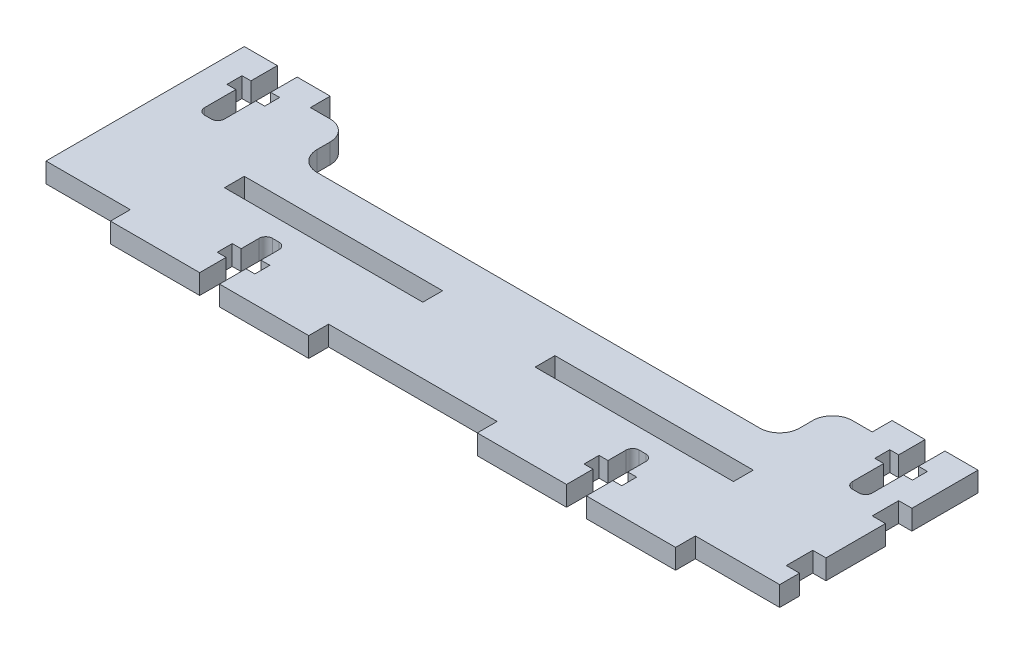
SolidWorks part; units mm, degrees
ref_plane "Plano frontal" through (0, 0, 0) normal (0, 0, 1) x (1, 0, 0)
ref_plane "Plano superior" through (0, 0, 0) normal (0, 1, 0) x (1, 0, 0)
ref_plane "Plano direito" through (0, 0, 0) normal (1, 0, 0) x (0, 0, -1)
sketch "Sketch1" plane through (0, 0, 0) normal (0, 1, 0) x (1, 0, 0)
  line L1 (-55.5, 15) -> (55.5, 15)
  line L2 (-55.5, 15) -> (-55.5, -15)
  line L3 (-55.5, -15) -> (55.5, -15)
  line L4 (55.5, 15) -> (55.5, -15)
  point P4 (0, 15)
  point P6 (-55.5, 0)
  dimension "D1" = 111
  dimension "D2" = 30
extrude "Boss-Extrude1" add sketch "Sketch1" along normal mid plane 3
sketch "Sketch2" plane through (0, 0, 0) normal (0, 1, 0) x (1, 0, 0)
  line L5 (-55.5, -15) -> (55.5, -15) construction
  line L6 (-42.75, -15) -> (-12.75, -15)
  line L7 (-42.75, -15) -> (-42.75, -18)
  line L8 (-42.75, -18) -> (-12.75, -18)
  line L9 (-12.75, -15) -> (-12.75, -18)
  line L10 (0, -1.65) -> (0, 1.65) construction
  line L11 (12.75, -15) -> (12.75, -18)
  line L12 (42.75, -18) -> (12.75, -18)
  line L13 (42.75, -15) -> (42.75, -18)
  line L14 (42.75, -15) -> (12.75, -15)
  line L15 (0, 15) -> (0, -15) construction
  line L16 (55.5, 15) -> (-55.5, 15) construction
  line L17 (-55.5, 15) -> (-55.5, -15) construction
  dimension "D1" = 3
  dimension "D2" = 30
  dimension "D3" = 12.75
  dimension "D4" = 12.75
extrude "Boss-Extrude2" add sketch "Sketch2" along normal mid plane 3
sketch "Sketch5" plane through (0, 0, 0) normal (0, 1, 0) x (1, 0, 0)
  line L0 (-42.75, -18) -> (-12.75, -18) construction
  line L1 (-29.25, -18) -> (-26.25, -18)
  line L2 (-29.25, -18) -> (-29.25, -14)
  line L3 (-28.25, -8) -> (-27.25, -8)
  line L4 (-26.25, -18) -> (-26.25, -14)
  line L6 (-29.25, -11.73) -> (-29.25, -9)
  line L7 (-30.5969, -11.73) -> (-29.25, -11.73)
  line L8 (-30.5969, -11.73) -> (-30.5969, -14)
  line L9 (-30.5969, -14) -> (-29.25, -14)
  line L10 (-24.9, -11.73) -> (-24.9, -14)
  line L11 (-26.25, -11.73) -> (-24.9, -11.73)
  line L12 (-26.25, -11.73) -> (-26.25, -9)
  line L13 (-26.25, -14) -> (-24.9, -14)
  line L14 (0, -1.65) -> (0, 1.65) construction
  line L15 (26.25, -14) -> (24.9, -14)
  line L16 (26.25, -11.73) -> (26.25, -9)
  line L17 (26.25, -11.73) -> (24.9, -11.73)
  line L18 (24.9, -11.73) -> (24.9, -14)
  line L19 (30.5969, -14) -> (29.25, -14)
  line L20 (30.5969, -11.73) -> (30.5969, -14)
  line L21 (30.5969, -11.73) -> (29.25, -11.73)
  line L22 (29.25, -11.73) -> (29.25, -9)
  line L23 (26.25, -18) -> (26.25, -14)
  line L24 (28.25, -8) -> (27.25, -8)
  line L25 (29.25, -18) -> (29.25, -14)
  line L26 (29.25, -18) -> (26.25, -18)
  arc A0 (-27.25, -8) -> (-26.25, -9) centre (-27.25, -9) cw
  arc A1 (-29.25, -9) -> (-28.25, -8) centre (-28.25, -9) cw
  arc A2 (29.25, -9) -> (28.25, -8) centre (28.25, -9) ccw
  arc A3 (27.25, -8) -> (26.25, -9) centre (27.25, -9) ccw
  point P8 (-27.75, -18)
  point P9 (-27.75, -18)
  point P22 (-29.25, -8)
  point P41 (29.25, -8)
  dimension "D8" = 1
  dimension "D2" = 10
  dimension "D3" = 3
  dimension "D4" = 2.27
  dimension "D5" = 1.3469
  dimension "D6" = 1.35
  dimension "D7" = 4
extrude "Cut-Extrude2" cut sketch "Sketch5" against normal through all both and the other way through all
sketch "Sketch6" plane through (0, 0, 0) normal (0, 1, 0) x (1, 0, 0)
  line L0 (55.5, -15) -> (55.5, 15) construction
  line L1 (55.5, -8) -> (53.5, -8)
  line L2 (55.5, -8) -> (55.5, -12)
  line L3 (55.5, -12) -> (53.5, -12)
  line L4 (53.5, -8) -> (53.5, -12)
  line L7 (42.75, -15) -> (55.5, -15) construction
  line L17 (53.5, 5) -> (55.5, 5)
  line L18 (53.5, 5) -> (53.5, 1)
  line L19 (53.5, 1) -> (55.5, 1)
  line L20 (55.5, 5) -> (55.5, 1)
  dimension "D1" = 4
  dimension "D2" = 2
  dimension "D3" = 3
  dimension "D4" = 9
extrude "Cut-Extrude3" cut sketch "Sketch6" against normal through all both and the other way through all
sketch "Sketch7" plane through (0, 1.5, 0) normal (0, 1, 0) x (1, 0, 0)
  line L9 (-38.5, -2) -> (-8.5, -2)
  line L10 (-38.5, -2) -> (-38.5, -5)
  line L11 (-38.5, -5) -> (-8.5, -5)
  line L12 (-8.5, -2) -> (-8.5, -5)
  line L13 (-27.25, -8) -> (-28.25, -8) construction
  line L14 (0, -1.65) -> (0, 1.65) construction
  line L19 (8.5, -2) -> (8.5, -5)
  line L20 (38.5, -5) -> (8.5, -5)
  line L21 (38.5, -2) -> (38.5, -5)
  line L22 (38.5, -2) -> (8.5, -2)
  line L23 (-55.5, 15) -> (-55.5, -15) construction
  line L25 (55.5, 5) -> (55.5, 15) construction
  dimension "D1" = 17
  dimension "D2" = 3
  dimension "D3" = 30
  dimension "D4" = 3
  dimension "D5" = 17
  dimension "D6" = 17
extrude "Cut-Extrude4" cut sketch "Sketch7" against normal through all both and the other way through all
sketch "Sketch8" plane through (0, 0, 0) normal (0, 1, 0) x (1, 0, 0)
  line L0 (55.5, 15) -> (-55.5, 15) construction
  line L1 (-42.5, 15) -> (42.5, 15)
  line L2 (-42.5, 15) -> (-42.5, 12)
  line L3 (-42.5, 12) -> (42.5, 12)
  line L4 (42.5, 15) -> (42.5, 12)
  line L8 (55.5, 5) -> (55.5, 15) construction
  point P8 (0, 12)
  dimension "D2" = 3
  dimension "D3" = 13
extrude "Cut-Extrude5" cut sketch "Sketch8" against normal through all both and the other way through all
sketch "Sketch10" plane through (0, 0, 0) normal (0, 1, 0) x (1, 0, 0)
  line L0 (-42.5, 12) -> (42.5, 12) construction
  line L1 (-36.5, 12) -> (36.5, 12)
  line L2 (-36.5, 12) -> (-36.5, 4)
  line L3 (-36.5, 4) -> (36.5, 4)
  line L4 (36.5, 12) -> (36.5, 4)
  line L5 (-42.5, 15) -> (-42.5, 12) construction
  line L6 (-8.5, -2) -> (-38.5, -2) construction
  point P6 (0, 4)
  dimension "D1" = 6
  dimension "D2" = 6
extrude "Cut-Extrude7" cut sketch "Sketch10" against normal through all both and the other way through all
fillet "Fillet1" radius 3 4 edges at (36.5, 0, -4) (36.5, 0, -12) (-36.5, 0, -4) (-36.5, 0, -12)
sketch "Sketch9" plane through (0, 0, 0) normal (0, 1, 0) x (1, 0, 0)
  line L0 (-42.5, 15) -> (-55.5, 15) construction
  line L1 (-50.5, 15) -> (-47.5, 15)
  line L2 (-50.5, 15) -> (-50.5, 11)
  line L3 (-49.5, 3) -> (-48.5, 3)
  line L4 (-47.5, 15) -> (-47.5, 11)
  line L5 (-55.5, 15) -> (-55.5, -15) construction
  line L6 (-51.85, 11) -> (-50.5, 11)
  line L7 (-51.85, 11) -> (-51.85, 8.73)
  line L8 (-51.85, 8.73) -> (-50.5, 8.73)
  line L9 (-46.15, 11) -> (-46.15, 8.73)
  line L11 (-47.5, 11) -> (-46.15, 11)
  line L12 (-50.5, 8.73) -> (-50.5, 4)
  line L13 (-47.5, 8.73) -> (-46.15, 8.73)
  line L14 (-47.5, 8.73) -> (-47.5, 4)
  line L15 (-55.5, 15) -> (-42.5, 15) construction
  line L16 (0, -1.65) -> (0, 1.65) construction
  line L17 (47.5, 8.73) -> (47.5, 4)
  line L18 (47.5, 8.73) -> (46.15, 8.73)
  line L19 (50.5, 8.73) -> (50.5, 4)
  line L20 (47.5, 11) -> (46.15, 11)
  line L21 (46.15, 11) -> (46.15, 8.73)
  line L22 (51.85, 8.73) -> (50.5, 8.73)
  line L23 (51.85, 11) -> (51.85, 8.73)
  line L24 (51.85, 11) -> (50.5, 11)
  line L25 (47.5, 15) -> (47.5, 11)
  line L26 (49.5, 3) -> (48.5, 3)
  line L27 (50.5, 15) -> (50.5, 11)
  line L28 (50.5, 15) -> (47.5, 15)
  line L29 (-42.5, 15) -> (-42.5, 12) construction
  arc A0 (-48.5, 3) -> (-47.5, 4) centre (-48.5, 4) ccw
  arc A1 (-50.5, 4) -> (-49.5, 3) centre (-49.5, 4) ccw
  arc A2 (50.5, 4) -> (49.5, 3) centre (49.5, 4) cw
  arc A3 (48.5, 3) -> (47.5, 4) centre (48.5, 4) cw
  point P20 (-50.5, 3)
  point P43 (50.5, 3)
  dimension "D8" = 1
  dimension "D1" = 12
  dimension "D2" = 2.27
  dimension "D3" = 1.35
  dimension "D4" = 1.35
  dimension "D5" = 4
  dimension "D6" = 3
  dimension "D7" = 5
  dimension "D9" = 13
  dimension "D10" = 5
extrude "Cut-Extrude6" cut sketch "Sketch9" against normal through all both and the other way through all
